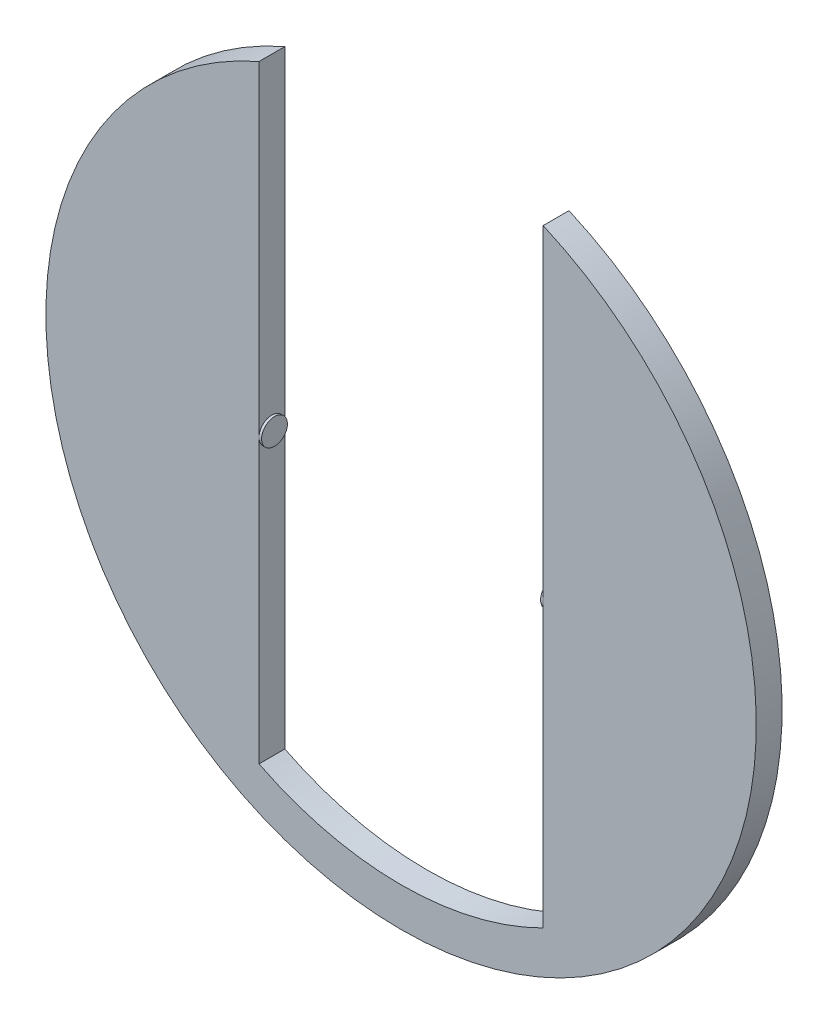
SolidWorks part; units mm, degrees
ref_plane "Ebene vorne" through (0, 0, 0) normal (0, 0, 1) x (1, 0, 0)
ref_plane "Ebene oben" through (0, 0, 0) normal (0, 1, 0) x (1, 0, 0)
ref_plane "Ebene rechts" through (0, 0, 0) normal (1, 0, 0) x (0, 0, -1)
sketch "Skizze1" plane through (0, 0, 0) normal (0, 0, 1) x (1, 0, 0)
  line L0 (0, 0) -> (90, 0) construction
  line L1 (0, 0) -> (115, 0) construction
  line L2 (0, 0) -> (0, 359.4514) construction
  line L7 (-110, 252.0417) -> (-110, -218.9178)
  line L8 (110, 252.0417) -> (110, -218.9178)
  line L9 (110, 212.0997) -> (110, -212.0997)
  line L10 (-288.8759, 272.0163) -> (-88.8759, 272.0163)
  line L11 (-288.8759, 272.0163) -> (-288.8759, 72.0163)
  line L12 (-288.8759, 72.0163) -> (-88.8759, 72.0163)
  line L13 (-88.8759, 272.0163) -> (-88.8759, 72.0163)
  arc A0 (-110, 252.0417) -> (110, 252.0417) centre (0, 0) ccw
  arc A1 (-110, -218.9178) -> (110, -218.9178) centre (0, 0) ccw
  point P16 (110, 0)
  dimension "D1" = 550
  dimension "D5" = 30
  dimension "D2" = 90
  dimension "D3" = 115
  dimension "D4" = 220
  dimension "D6" = 200
  dimension "D7" = 200
extrude "Aufsatz-Linear austragen1" add sketch "Skizze1" along normal blind 20
sketch "Skizze2" plane through (-110, 0, 0) normal (1, 0, 0) x (0, 0, -1)
  line L0 (0, 0) -> (-20, 0) construction
  line L1 (-20, 252.0417) -> (-20, -275) construction
  circle A0 centre (-10, 0) radius 10
extrude "Aufsatz-Linear austragen2" add sketch "Skizze2" along normal blind 2
mirror "Spiegeln1" about plane through (0, 0, 0) normal (1, 0, 0) of "Aufsatz-Linear austragen2"
